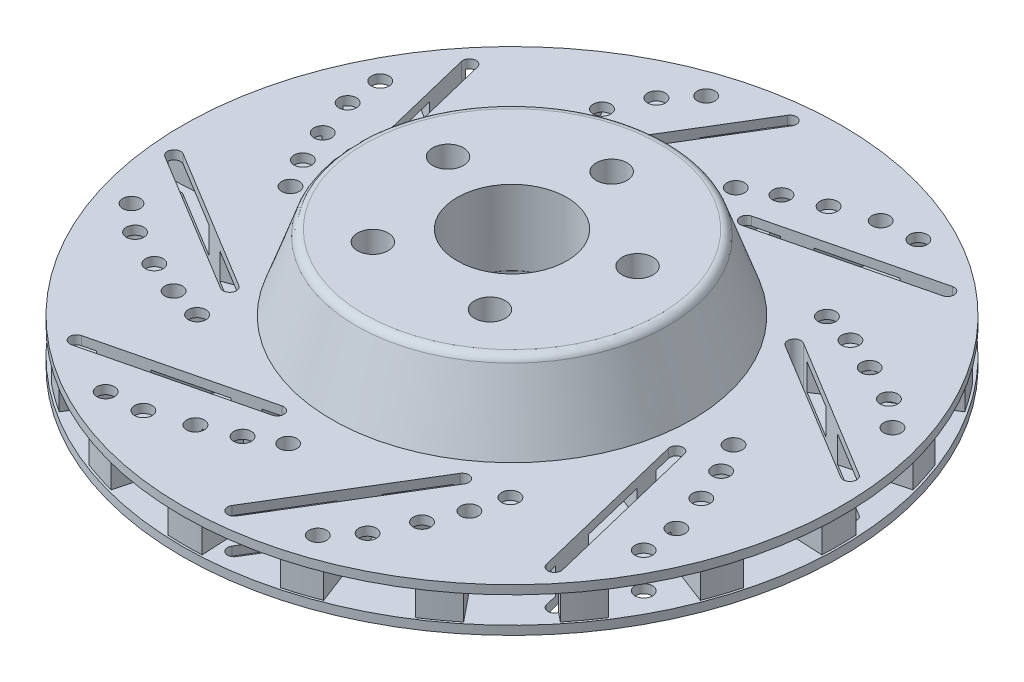
SolidWorks part; units mm, degrees
ref_plane "Front Plane" through (0, 0, 0) normal (0, 0, 1) x (1, 0, 0)
ref_plane "Top Plane" through (0, 0, 0) normal (0, 1, 0) x (1, 0, 0)
ref_plane "Right Plane" through (0, 0, 0) normal (1, 0, 0) x (0, 0, -1)
sketch "Sketch1" plane through (0, 0, 0) normal (0, 1, 0) x (1, 0, 0)
  circle A0 centre (0, 0) radius 150
  dimension "D1" = 300
extrude "Boss-Extrude1" add sketch "Sketch1" along normal blind 4
sketch "Sketch2" plane through (0, 4, 0) normal (0, 1, 0) x (1, 0, 0)
  line L0 (0, 164.5803) -> (0, -149) construction
  line L1 (-4.2915, 81.8876) -> (-7.7981, 148.7958)
  line L2 (4.2915, 81.8876) -> (7.7981, 148.7958)
  line L3 (21.2232, 79.2059) -> (38.564, 143.9229)
  line L4 (29.3862, 76.5536) -> (53.3968, 139.1035)
  line L5 (44.6604, 68.771) -> (81.1512, 124.9619)
  line L6 (51.6043, 63.726) -> (93.7687, 115.7947)
  line L7 (63.726, 51.6043) -> (115.7947, 93.7687)
  line L8 (68.771, 44.6604) -> (124.9619, 81.1512)
  line L9 (76.5536, 29.3862) -> (139.1035, 53.3968)
  line L10 (79.2059, 21.2232) -> (143.9229, 38.564)
  line L11 (81.8876, 4.2915) -> (148.7958, 7.7981)
  line L12 (81.8876, -4.2915) -> (148.7958, -7.7981)
  line L13 (79.2059, -21.2232) -> (143.9229, -38.564)
  line L14 (76.5536, -29.3862) -> (139.1035, -53.3968)
  line L15 (68.771, -44.6604) -> (124.9619, -81.1512)
  line L16 (63.726, -51.6043) -> (115.7947, -93.7687)
  line L17 (51.6043, -63.726) -> (93.7687, -115.7947)
  line L18 (44.6604, -68.771) -> (81.1512, -124.9619)
  line L19 (29.3862, -76.5536) -> (53.3968, -139.1035)
  line L20 (21.2232, -79.2059) -> (38.564, -143.9229)
  line L21 (4.2915, -81.8876) -> (7.7981, -148.7958)
  line L22 (-4.2915, -81.8876) -> (-7.7981, -148.7958)
  line L23 (-21.2232, -79.2059) -> (-38.564, -143.9229)
  line L24 (-29.3862, -76.5536) -> (-53.3968, -139.1035)
  line L25 (-44.6604, -68.771) -> (-81.1512, -124.9619)
  line L26 (-51.6043, -63.726) -> (-93.7687, -115.7947)
  line L27 (-63.726, -51.6043) -> (-115.7947, -93.7687)
  line L28 (-68.771, -44.6604) -> (-124.9619, -81.1512)
  line L29 (-76.5536, -29.3862) -> (-139.1035, -53.3968)
  line L30 (-79.2059, -21.2232) -> (-143.9229, -38.564)
  line L31 (-81.8876, -4.2915) -> (-148.7958, -7.7981)
  line L32 (-81.8876, 4.2915) -> (-148.7958, 7.7981)
  line L33 (-79.2059, 21.2232) -> (-143.9229, 38.564)
  line L34 (-76.5536, 29.3862) -> (-139.1035, 53.3968)
  line L35 (-68.771, 44.6604) -> (-124.9619, 81.1512)
  line L36 (-63.726, 51.6043) -> (-115.7947, 93.7687)
  line L37 (-51.6043, 63.726) -> (-93.7687, 115.7947)
  line L38 (-44.6604, 68.771) -> (-81.1512, 124.9619)
  line L39 (-29.3862, 76.5536) -> (-53.3968, 139.1035)
  line L40 (-21.2232, 79.2059) -> (-38.564, 143.9229)
  arc A0 (-81.8876, 4.2915) -> (-81.8876, -4.2915) centre (0, 0) ccw
  arc A1 (-81.1512, 124.9619) -> (-93.7687, 115.7947) centre (0, 0) ccw
  arc A2 (-76.5536, 29.3862) -> (-79.2059, 21.2232) centre (0, 0) ccw
  arc A3 (-63.726, 51.6043) -> (-68.771, 44.6604) centre (0, 0) ccw
  arc A4 (-44.6604, 68.771) -> (-51.6043, 63.726) centre (0, 0) ccw
  arc A5 (-21.2232, 79.2059) -> (-29.3862, 76.5536) centre (0, 0) ccw
  arc A6 (-29.3862, -76.5536) -> (-21.2232, -79.2059) centre (0, 0) ccw
  arc A7 (-51.6043, -63.726) -> (-44.6604, -68.771) centre (0, 0) ccw
  arc A8 (-68.771, -44.6604) -> (-63.726, -51.6043) centre (0, 0) ccw
  arc A9 (-79.2059, -21.2232) -> (-76.5536, -29.3862) centre (0, 0) ccw
  arc A10 (-4.2915, -81.8876) -> (4.2915, -81.8876) centre (0, 0) ccw
  arc A11 (21.2232, -79.2059) -> (29.3862, -76.5536) centre (0, 0) ccw
  arc A12 (44.6604, -68.771) -> (51.6043, -63.726) centre (0, 0) ccw
  arc A13 (63.726, -51.6043) -> (68.771, -44.6604) centre (0, 0) ccw
  arc A14 (76.5536, -29.3862) -> (79.2059, -21.2232) centre (0, 0) ccw
  arc A15 (81.8876, -4.2915) -> (81.8876, 4.2915) centre (0, 0) ccw
  arc A16 (79.2059, 21.2232) -> (76.5536, 29.3862) centre (0, 0) ccw
  arc A17 (68.771, 44.6604) -> (63.726, 51.6043) centre (0, 0) ccw
  arc A18 (51.6043, 63.726) -> (44.6604, 68.771) centre (0, 0) ccw
  arc A19 (29.3862, 76.5536) -> (21.2232, 79.2059) centre (0, 0) ccw
  arc A20 (4.2915, 81.8876) -> (-4.2915, 81.8876) centre (0, 0) ccw
  arc A21 (-115.7947, 93.7687) -> (-124.9619, 81.1512) centre (0, 0) ccw
  arc A22 (-139.1035, 53.3968) -> (-143.9229, 38.564) centre (0, 0) ccw
  arc A23 (-148.7958, 7.7981) -> (-148.7958, -7.7981) centre (0, 0) ccw
  arc A24 (-143.9229, -38.564) -> (-139.1035, -53.3968) centre (0, 0) ccw
  arc A25 (-124.9619, -81.1512) -> (-115.7947, -93.7687) centre (0, 0) ccw
  arc A26 (-38.564, 143.9229) -> (-53.3968, 139.1035) centre (0, 0) ccw
  arc A27 (7.7981, 148.7958) -> (-7.7981, 148.7958) centre (0, 0) ccw
  arc A28 (53.3968, 139.1035) -> (38.564, 143.9229) centre (0, 0) ccw
  arc A29 (93.7687, 115.7947) -> (81.1512, 124.9619) centre (0, 0) ccw
  arc A30 (124.9619, 81.1512) -> (115.7947, 93.7687) centre (0, 0) ccw
  arc A31 (143.9229, 38.564) -> (139.1035, 53.3968) centre (0, 0) ccw
  arc A32 (148.7958, -7.7981) -> (148.7958, 7.7981) centre (0, 0) ccw
  arc A33 (139.1035, -53.3968) -> (143.9229, -38.564) centre (0, 0) ccw
  arc A34 (115.7947, -93.7687) -> (124.9619, -81.1512) centre (0, 0) ccw
  arc A35 (81.1512, -124.9619) -> (93.7687, -115.7947) centre (0, 0) ccw
  arc A36 (38.564, -143.9229) -> (53.3968, -139.1035) centre (0, 0) ccw
  arc A37 (-7.7981, -148.7958) -> (7.7981, -148.7958) centre (0, 0) ccw
  arc A38 (-53.3968, -139.1035) -> (-38.564, -143.9229) centre (0, 0) ccw
  arc A39 (-93.7687, -115.7947) -> (-81.1512, -124.9619) centre (0, 0) ccw
  point P87 (0, 0)
  dimension "D1" = 164
  dimension "D2" = 298
  dimension "D3" = 3
  dimension "D4" = 20
extrude "Boss-Extrude3" add sketch "Sketch2" along normal blind 12
sketch "Sketch4" plane through (0, 16, 0) normal (0, 1, 0) x (1, 0, 0)
  circle A0 centre (0, 0) radius 150
  dimension "D1" = 300
extrude "Boss-Extrude4" add sketch "Sketch4" along normal blind 4
sketch "Sketch5" plane through (0, 0, 0) normal (0, 0, 1) x (1, 0, 0)
  line L0 (0, 54.0887) -> (0, 0.6091) construction
  line L1 (0, 20.0887) -> (-82, 20)
  line L2 (0, 20.0887) -> (0, 54.0887)
  line L3 (0, 54.0887) -> (-70, 54.0887)
  line L4 (-70, 54.0887) -> (-82, 20)
  dimension "D1" = 82
  dimension "D2" = 34
  dimension "D3" = 70
  dimension "D4" = 70.545
revolve "Revolve1" add sketch "Sketch5" angle 360 about L0
fillet "Fillet1" radius 4 1 edges at (0, 54.0887, 70)
sketch "Sketch6" plane through (0, 54.0887, 0) normal (0, 1, 0) x (1, 0, 0)
  circle A0 centre (0, 0) radius 25
  dimension "D1" = 50
extrude "Cut-Extrude1" cut sketch "Sketch6" against normal through all
sketch "Sketch7" plane through (0, 54.0887, 0) normal (0, 1, 0) x (1, 0, 0)
  circle A0 centre (0, 45.3494) radius 7
  circle A1 centre (43.1299, 14.0137) radius 7
  circle A2 centre (26.6557, -36.6885) radius 7
  circle A3 centre (-26.6557, -36.6885) radius 7
  circle A4 centre (-43.1299, 14.0137) radius 7
  point P12 (0, 0)
  dimension "D1" = 14
  dimension "D2" = 5
extrude "Cut-Extrude2" cut sketch "Sketch7" against normal blind 31
sketch "Sketch9" plane through (0, 20, 0) normal (0, 1, 0) x (1, 0, 0)
  line L0 (-52.9077, 75.5824) -> (-13.6865, 140.1338) construction
  line L1 (-55.4988, 77.1567) -> (-16.2777, 141.7082)
  line L2 (-50.3165, 74.008) -> (-11.0954, 138.5595)
  line L3 (16.0334, 90.8562) -> (89.4117, 108.7674) construction
  line L4 (15.3145, 93.8016) -> (88.6928, 111.7129)
  line L5 (16.7524, 87.9108) -> (90.1307, 105.822)
  line L6 (75.5824, 52.9077) -> (140.1338, 13.6865) construction
  line L7 (77.1567, 55.4988) -> (141.7082, 16.2777)
  line L8 (74.008, 50.3165) -> (138.5595, 11.0954)
  line L9 (90.8562, -16.0334) -> (108.7674, -89.4117) construction
  line L10 (93.8016, -15.3145) -> (111.7129, -88.6928)
  line L11 (87.9108, -16.7524) -> (105.822, -90.1307)
  line L12 (52.9077, -75.5824) -> (13.6865, -140.1338) construction
  line L13 (55.4988, -77.1567) -> (16.2777, -141.7082)
  line L14 (50.3165, -74.008) -> (11.0954, -138.5595)
  line L15 (-16.0334, -90.8562) -> (-89.4117, -108.7674) construction
  line L16 (-15.3145, -93.8016) -> (-88.6928, -111.7129)
  line L17 (-16.7524, -87.9108) -> (-90.1307, -105.822)
  line L18 (-75.5824, -52.9077) -> (-140.1338, -13.6865) construction
  line L19 (-77.1567, -55.4988) -> (-141.7082, -16.2777)
  line L20 (-74.008, -50.3165) -> (-138.5595, -11.0954)
  line L21 (-90.8562, 16.0334) -> (-108.7674, 89.4117) construction
  line L22 (-93.8016, 15.3145) -> (-111.7129, 88.6928)
  line L23 (-87.9108, 16.7524) -> (-105.822, 90.1307)
  arc A0 (-55.4988, 77.1567) -> (-50.3165, 74.008) centre (-52.9077, 75.5824) ccw
  arc A1 (-11.0954, 138.5595) -> (-16.2777, 141.7082) centre (-13.6865, 140.1338) ccw
  circle A2 centre (-71.3002, 72.0321) radius 4
  circle A3 centre (-67.309, 86.7195) radius 4
  circle A4 centre (-60.9232, 101.8859) radius 4
  circle A5 centre (-52.9077, 118.6487) radius 4
  circle A6 centre (-42.4042, 130.7818) radius 4
  circle A7 centre (13.7253, 108.9146) radius 4
  circle A8 centre (28.965, 115.1234) radius 4
  circle A9 centre (46.486, 121.3087) radius 4
  circle A10 centre (62.4924, 122.461) radius 4
  circle A11 centre (0.5176, 101.3512) radius 4
  arc A12 (15.3145, 93.8016) -> (16.7524, 87.9108) centre (16.0334, 90.8562) ccw
  arc A13 (90.1307, 105.822) -> (88.6928, 111.7129) centre (89.4117, 108.7674) ccw
  circle A14 centre (86.7195, 67.309) radius 4
  circle A15 centre (101.8859, 60.9232) radius 4
  circle A16 centre (118.6487, 52.9077) radius 4
  circle A17 centre (130.7818, 42.4042) radius 4
  circle A18 centre (72.0321, 71.3002) radius 4
  arc A19 (77.1567, 55.4988) -> (74.008, 50.3165) centre (75.5824, 52.9077) ccw
  arc A20 (138.5595, 11.0954) -> (141.7082, 16.2777) centre (140.1338, 13.6865) ccw
  circle A21 centre (108.9146, -13.7253) radius 4
  circle A22 centre (115.1234, -28.965) radius 4
  circle A23 centre (121.3087, -46.486) radius 4
  circle A24 centre (122.461, -62.4924) radius 4
  circle A25 centre (101.3512, -0.5176) radius 4
  arc A26 (93.8016, -15.3145) -> (87.9108, -16.7524) centre (90.8562, -16.0334) ccw
  arc A27 (105.822, -90.1307) -> (111.7129, -88.6928) centre (108.7674, -89.4117) ccw
  circle A28 centre (67.309, -86.7195) radius 4
  circle A29 centre (60.9232, -101.8859) radius 4
  circle A30 centre (52.9077, -118.6487) radius 4
  circle A31 centre (42.4042, -130.7818) radius 4
  circle A32 centre (71.3002, -72.0321) radius 4
  arc A33 (55.4988, -77.1567) -> (50.3165, -74.008) centre (52.9077, -75.5824) ccw
  arc A34 (11.0954, -138.5595) -> (16.2777, -141.7082) centre (13.6865, -140.1338) ccw
  circle A35 centre (-13.7253, -108.9146) radius 4
  circle A36 centre (-28.965, -115.1234) radius 4
  circle A37 centre (-46.486, -121.3087) radius 4
  circle A38 centre (-62.4924, -122.461) radius 4
  circle A39 centre (-0.5176, -101.3512) radius 4
  arc A40 (-15.3145, -93.8016) -> (-16.7524, -87.9108) centre (-16.0334, -90.8562) ccw
  arc A41 (-90.1307, -105.822) -> (-88.6928, -111.7129) centre (-89.4117, -108.7674) ccw
  circle A42 centre (-86.7195, -67.309) radius 4
  circle A43 centre (-101.8859, -60.9232) radius 4
  circle A44 centre (-118.6487, -52.9077) radius 4
  circle A45 centre (-130.7818, -42.4042) radius 4
  circle A46 centre (-72.0321, -71.3002) radius 4
  arc A47 (-77.1567, -55.4988) -> (-74.008, -50.3165) centre (-75.5824, -52.9077) ccw
  arc A48 (-138.5595, -11.0954) -> (-141.7082, -16.2777) centre (-140.1338, -13.6865) ccw
  circle A49 centre (-108.9146, 13.7253) radius 4
  circle A50 centre (-115.1234, 28.965) radius 4
  circle A51 centre (-121.3087, 46.486) radius 4
  circle A52 centre (-122.461, 62.4924) radius 4
  circle A53 centre (-101.3512, 0.5176) radius 4
  arc A54 (-93.8016, 15.3145) -> (-87.9108, 16.7524) centre (-90.8562, 16.0334) ccw
  arc A55 (-105.822, 90.1307) -> (-111.7129, 88.6928) centre (-108.7674, 89.4117) ccw
  point P2 (-33.2971, 107.8581)
  point P22 (52.7226, 99.8118)
  point P39 (107.8581, 33.2971)
  point P56 (99.8118, -52.7226)
  point P73 (33.2971, -107.8581)
  point P90 (-52.7226, -99.8118)
  point P107 (-107.8581, -33.2971)
  point P124 (-99.8118, 52.7226)
  point P139 (0, 0)
  dimension "D1" = 8
  dimension "D2" = 8
  dimension "D3" = 8
  dimension "D4" = 8
  dimension "D5" = 8
  dimension "D6" = 8
extrude "Cut-Extrude3" cut sketch "Sketch9" against normal through all both and the other way through all
